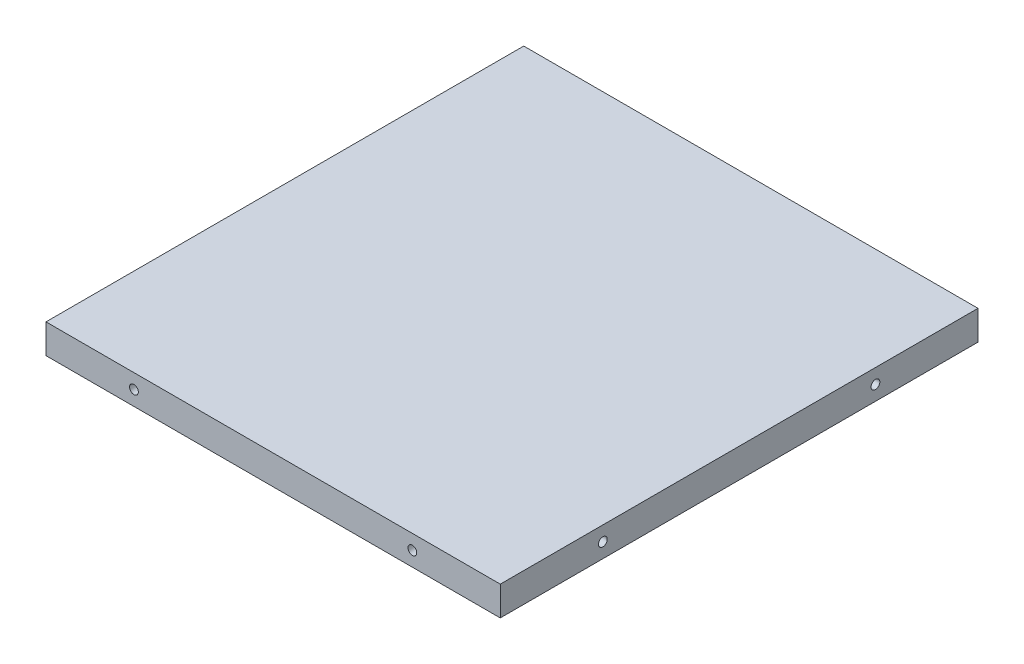
SolidWorks part; units mm, degrees
ref_plane "Front Plane" through (0, 0, 0) normal (0, 0, 1) x (1, 0, 0)
ref_plane "Top Plane" through (0, 0, 0) normal (0, 1, 0) x (1, 0, 0)
ref_plane "Right Plane" through (0, 0, 0) normal (1, 0, 0) x (0, 0, -1)
sketch "Sketch1" plane through (0, 0, 0) normal (0, 1, 0) x (1, 0, 0)
  line L1 (0, 0) -> (155, 0)
  line L2 (0, 0) -> (0, 163)
  line L3 (0, 163) -> (155, 163)
  line L4 (155, 0) -> (155, 163)
  dimension "D1" = 155
  dimension "D2" = 163
extrude "Boss-Extrude1" add sketch "Sketch1" along normal blind 10 contours L3 L4 L1 L2
sketch "Sketch2" plane through (0, 0, -163) normal (0, 0, -1) x (-1, 0, 0)
  line L0 (-155, 5) -> (0, 5) construction
  line L1 (-155, 10) -> (-155, 0) construction
  line L2 (0, 10) -> (0, 0) construction
  line L3 (-77.5, 10) -> (-77.5, 0) construction
  line L4 (0, 10) -> (-155, 10) construction
  line L5 (0, 0) -> (-155, 0) construction
  circle A0 centre (-125, 5) radius 1.5
  circle A1 centre (-30, 5) radius 1.5
  dimension "D1" = 3
  dimension "D2" = 30
extrude "Cut-Extrude1" cut sketch "Sketch2" against normal blind 20
ref_plane "Plane1" through (0, 0, -81.5) normal (0, 0, -1) x (-1, 0, 0)
mirror "Mirror1" about plane through (0, 0, -81.5) normal (0, 0, -1) of "Cut-Extrude1"
sketch "Sketch3" plane through (155, 0, 0) normal (1, 0, 0) x (0, 0, -1)
  line L0 (0, 5) -> (163, 5) construction
  line L1 (0, 10) -> (0, 0) construction
  line L2 (163, 10) -> (163, 0) construction
  line L3 (81.5, -11) -> (81.5, 11) construction
  circle A0 centre (35, 5) radius 1.5
  circle A1 centre (128, 5) radius 1.5
  point P7 (163, 5)
  dimension "D1" = 3
  dimension "D2" = 35
extrude "Cut-Extrude2" cut sketch "Sketch3" against normal through all both and the other way through all
